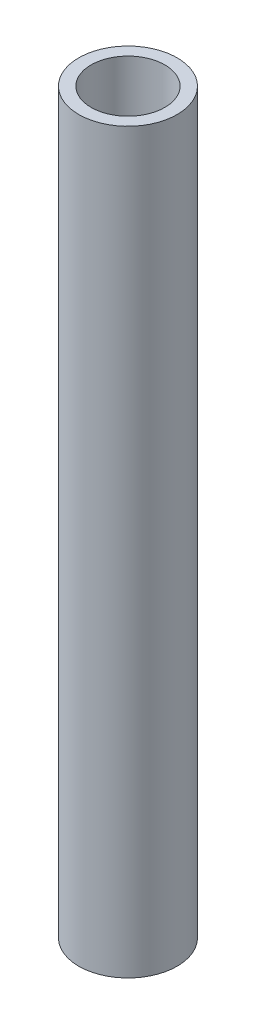
SolidWorks part; units mm, degrees
material "Hexcel AS4C (3000 丝)"
ref_plane "前视基准面" through (0, 0, 0) normal (0, 0, 1) x (1, 0, 0)
ref_plane "上视基准面" through (0, 0, 0) normal (0, 1, 0) x (1, 0, 0)
ref_plane "右视基准面" through (0, 0, 0) normal (1, 0, 0) x (0, 0, -1)
sketch "草图1" plane through (0, 0, 0) normal (0, 1, 0) x (1, 0, 0)
  line L0 (-33.8272, 0) -> (33.8272, 0) construction
  line L1 (0, -24.9545) -> (0, 24.9545) construction
  circle A0 centre (0, 0) radius 4
  circle A1 centre (0, 0) radius 3
  point P4 (0, 0)
  point P8 (0, 0)
  dimension "D1" = 8
  dimension "D2" = 6
extrude "凸台-拉伸1" add sketch "草图1" along normal blind 60
